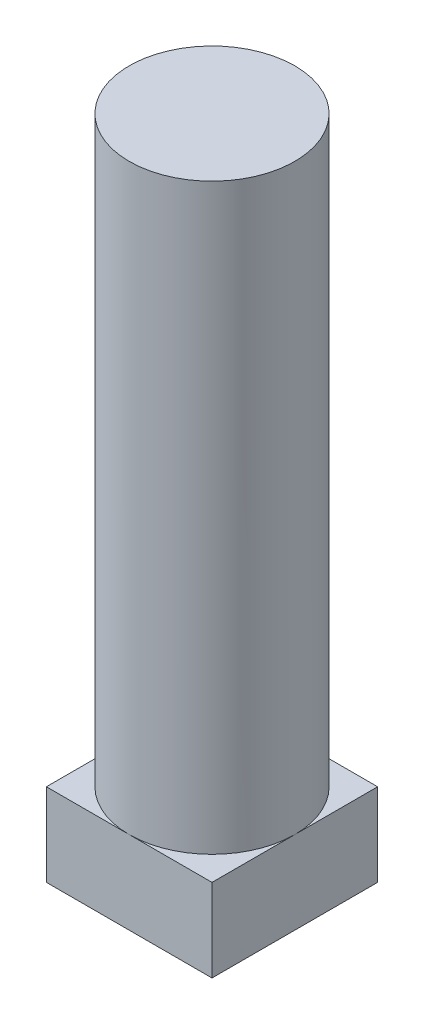
SolidWorks part; units mm, degrees
ref_plane "Front Plane" through (0, 0, 0) normal (0, 0, 1) x (1, 0, 0)
ref_plane "Top Plane" through (0, 0, 0) normal (0, 1, 0) x (1, 0, 0)
ref_plane "Right Plane" through (0, 0, 0) normal (1, 0, 0) x (0, 0, -1)
sketch "Sketch1" plane through (0, 0, 0) normal (0, 1, 0) x (1, 0, 0)
  line L1 (-2.5, -2.5) -> (2.5, -2.5)
  line L2 (-2.5, -2.5) -> (-2.5, 2.5)
  line L3 (-2.5, 2.5) -> (2.5, 2.5)
  line L4 (2.5, -2.5) -> (2.5, 2.5)
  line L5 (-2.5, -2.5) -> (2.5, 2.5) construction
  line L6 (-2.5, 2.5) -> (2.5, -2.5) construction
  point P0 (0, 0)
  dimension "D1" = 5
extrude "Boss-Extrude1" add sketch "Sketch1" along normal blind 2.5 contours L2 L3 L4 L1
sketch "Sketch2" plane through (0, 2.5, 0) normal (0, 1, 0) x (1, 0, 0)
  line L0 (2.5, -2.5) -> (2.5, 2.5) construction
  circle A0 centre (0, 0) radius 2.5
extrude "Boss-Extrude2" add sketch "Sketch2" along normal blind 17.6
equation "\"a\"= 1"
equation "\"b\"= 1"
equation "\"c\"= 1"
equation "\"d\"= 1"
equation "\"e\"= 1"
equation "\"x\"= 1"
equation "\"y\"= 1"
equation "\"z\"= 1"
